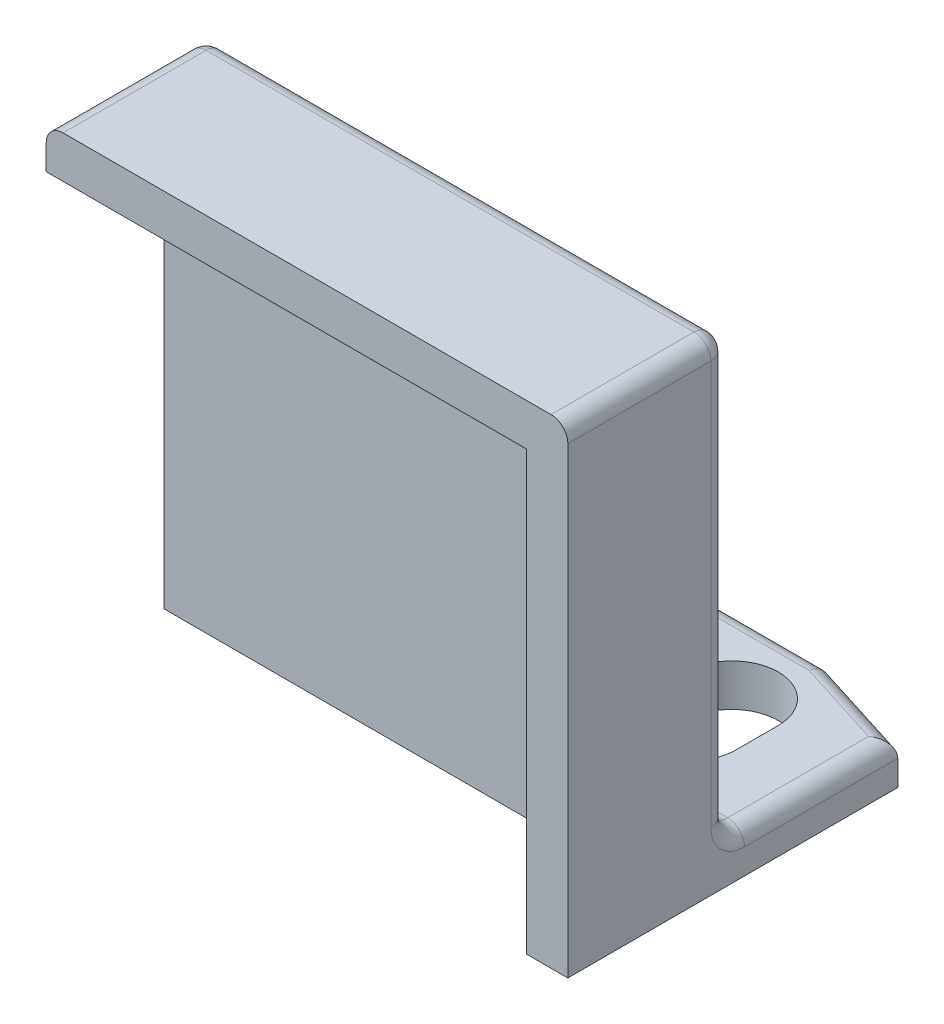
SolidWorks part; units mm, degrees
ref_plane "Front Plane" through (0, 0, 0) normal (0, 0, 1) x (1, 0, 0)
ref_plane "Top Plane" through (0, 0, 0) normal (0, 1, 0) x (1, 0, 0)
ref_plane "Right Plane" through (0, 0, 0) normal (1, 0, 0) x (0, 0, -1)
sketch "Sketch1" plane through (0, 0, 0) normal (0, 1, 0) x (1, 0, 0)
  line L0 (-19.685, 12.8386) -> (-12.065, 15.24)
  line L1 (-19.685, 15.24) -> (19.685, 15.24)
  line L2 (-19.685, 15.24) -> (-19.685, 0)
  line L3 (-19.685, 0) -> (19.685, 0)
  line L4 (19.685, 15.24) -> (19.685, 0)
  line L5 (0, 0) -> (0, 15.24) construction
  line L6 (-10.795, 9.2075) -> (-10.795, 6.0325) construction
  line L7 (-7.295, 9.2075) -> (-7.295, 6.0325)
  line L8 (-14.295, 9.2075) -> (-14.295, 6.0325)
  line L9 (10.795, 9.2075) -> (10.795, 6.0325) construction
  line L10 (7.295, 9.2075) -> (7.295, 6.0325)
  line L11 (14.295, 9.2075) -> (14.295, 6.0325)
  line L12 (19.685, 12.8386) -> (12.065, 15.24)
  arc A0 (-7.295, 9.2075) -> (-14.295, 9.2075) centre (-10.795, 9.2075) ccw
  arc A1 (-14.295, 6.0325) -> (-7.295, 6.0325) centre (-10.795, 6.0325) ccw
  arc A2 (7.295, 9.2075) -> (14.295, 9.2075) centre (10.795, 9.2075) cw
  arc A3 (14.295, 6.0325) -> (7.295, 6.0325) centre (10.795, 6.0325) cw
  point P4 (0, 0)
  point P12 (-10.795, 7.62)
  point P21 (10.795, 7.62)
  point P28 (-19.685, 7.62)
  dimension "D5" = 3.5
  dimension "D7" = 7.62
  dimension "D1" = 15.24
  dimension "D2" = 39.37
  dimension "D3" = 2.4014
  dimension "D4" = 3.175
  dimension "D6" = 8.89
extrude "Boss-Extrude1" add sketch "Sketch1" along normal blind 3.175 contours L4 L12 L1 L0 L2 L3 A1 L8 A0 L7 L11 A3 L10 A2
sketch "Sketch2" plane through (0, 0, 0) normal (0, 1, 0) x (1, 0, 0)
  line L0 (19.685, 12.8386) -> (19.685, 0) construction
  line L1 (-19.685, 0) -> (19.685, 0)
  line L2 (-19.685, 0) -> (-19.685, -3.175)
  line L3 (-19.685, -3.175) -> (19.685, -3.175)
  line L4 (19.685, 0) -> (19.685, -3.175)
  dimension "D1" = 3.175
extrude "Boss-Extrude2" add sketch "Sketch2" along normal blind 33.02
sketch "Sketch3" plane through (0, 33.02, 0) normal (0, 1, 0) x (1, 0, 0)
  line L1 (-19.685, -3.175) -> (19.685, -3.175)
  line L2 (-19.685, -3.175) -> (-19.685, -12.065)
  line L3 (-19.685, -12.065) -> (19.685, -12.065)
  line L4 (-19.685, 0) -> (-19.685, -3.175)
  line L5 (-19.685, -3.175) -> (19.685, -3.175)
  line L6 (19.685, -3.175) -> (19.685, 0)
  line L7 (19.685, 0) -> (-19.685, 0)
  line L8 (-19.685, 0) -> (-19.685, -3.175)
  line L9 (-19.685, -3.175) -> (19.685, -3.175)
  line L10 (19.685, -3.175) -> (19.685, 0)
  line L11 (19.685, 0) -> (-19.685, 0)
  line L12 (19.685, -3.175) -> (19.685, -12.065)
  line M9 (-19.685, 0) -> (-19.685, -3.175)
  line M10 (-19.685, -3.175) -> (19.685, -3.175)
  line M11 (19.685, -3.175) -> (19.685, 0)
  line M12 (19.685, 0) -> (-19.685, 0)
  dimension "D2" = 8.89
  dimension "D1" = 0
extrude "Boss-Extrude3" add sketch "Sketch3" along normal blind 3.175 contours L12 L2 L3 M10 | M12 M9 M10 M11
sketch "Sketch4" plane through (19.685, 0, 0) normal (1, 0, 0) x (0, 0, -1)
  line L1 (-12.065, 33.02) -> (-3.175, 33.02)
  line L2 (-12.065, 33.02) -> (-12.065, 0)
  line L3 (-12.065, 0) -> (-3.175, 0)
  line L4 (-3.175, 33.02) -> (-3.175, 0)
extrude "Boss-Extrude4" add sketch "Sketch4" against normal blind 3.1242
ref_plane "Plane1" through (0, 0, 0) normal (1, 0, 0) x (0, 0, -1)
sketch "Sketch6" plane through (0, 0, 0) normal (1, 0, 0) x (0, 0, -1)
  line L0 (0, 33.1296) -> (13.4535, 3.175)
  line L1 (0, 36.195) -> (0, 3.175) construction
  line L2 (12.8386, 3.175) -> (15.24, 3.175) construction
rib "Rib1" sketch "Sketch6" sketch "Sketch6" thickness 2.54 extrusion direction parallel to sketch draft on no parameters "D1"=2.54
fillet "Fillet1" radius 1.27 17 edges at (-1.27, 18.1523, 0) (1.27, 18.1523, 0) (-1.27, 3.175, -6.7268) (1.27, 3.175, -6.7268) (-10.4775, 3.175, 0) (10.4775, 3.175, 0) (0, 33.1296, 0) (-19.685, 19.685, 0) (-19.685, 3.175, -6.4193) (-15.875, 3.175, -14.0393) (0, 3.175, -15.24) (15.875, 3.175, -14.0393) (19.685, 3.175, -6.4193) (19.685, 19.685, 0) (-19.685, 36.195, 6.0325) (0, 36.195, 0) (19.685, 36.195, 6.0325)
